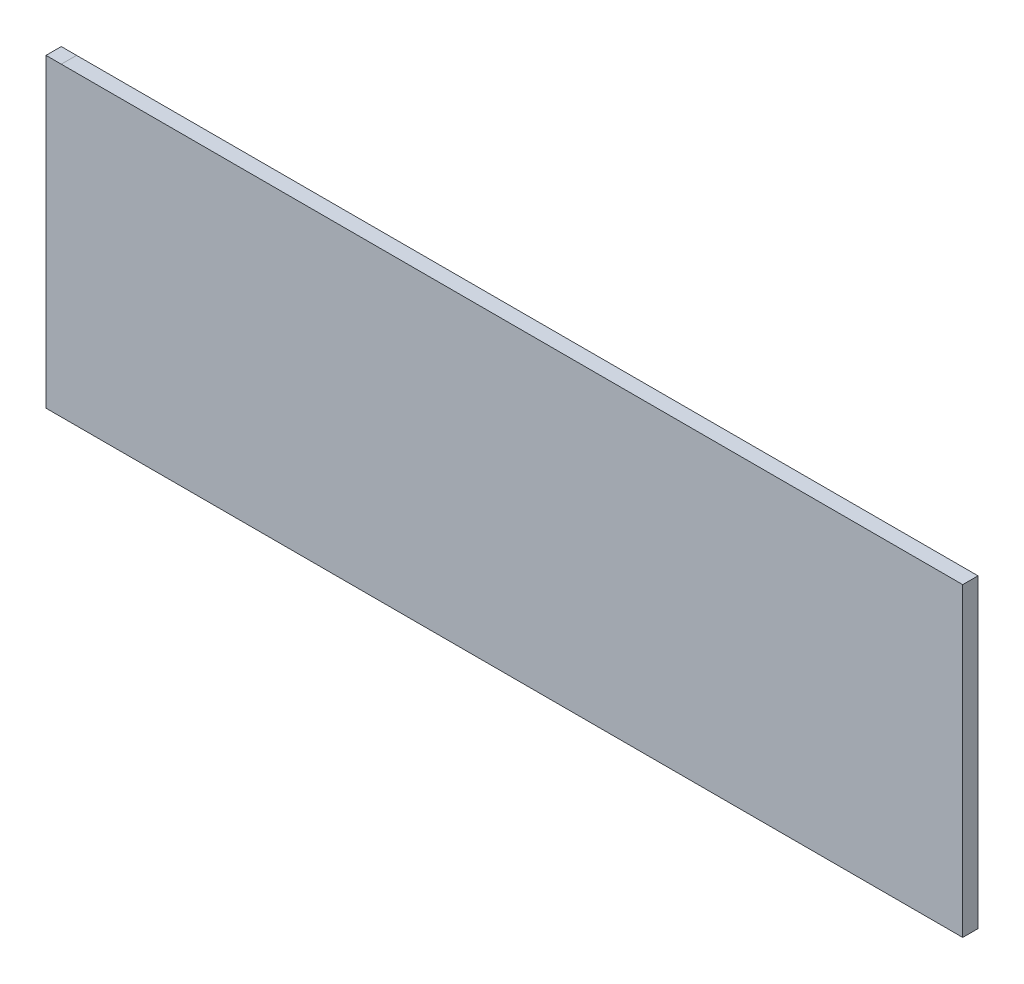
SolidWorks part; units mm, degrees
ref_plane "Front Plane" through (0, 0, 0) normal (0, 0, 1) x (1, 0, 0)
ref_plane "Top Plane" through (0, 0, 0) normal (0, 1, 0) x (1, 0, 0)
ref_plane "Right Plane" through (0, 0, 0) normal (1, 0, 0) x (0, 0, -1)
sketch "Sketch1" plane through (0, 0, 0) normal (0, 0, 1) x (1, 0, 0)
  line L1 (0, 0) -> (1200, 0)
  line L2 (0, 0) -> (0, 400)
  line L3 (0, 400) -> (1200, 400)
  line L4 (1200, 0) -> (1200, 400)
  dimension "D1" = 1200
  dimension "D2" = 400
extrude "Boss-Extrude1" add sketch "Sketch1" along normal blind 20
sketch "Sketch3" plane through (0, 400, 0) normal (0, 1, 0) x (1, 0, 0)
  line L0 (20, 0) -> (20, -20)
  line L1 (1200, 0) -> (0, 0) construction
  line L2 (1200, -20) -> (0, -20) construction
  line L3 (0, -20) -> (0, 0) construction
  dimension "D1" = 20
split line "Split Line1"
sketch "Sketch4" plane through (0, 0, 0) normal (0, -1, 0) x (1, 0, 0)
  line L0 (1180, 20) -> (1180, 0)
  line L1 (0, 20) -> (1200, 20) construction
  line L2 (1200, 20) -> (1200, 0) construction
  line L3 (0, 0) -> (1200, 0) construction
  dimension "D1" = 20
split line "Split Line2"
